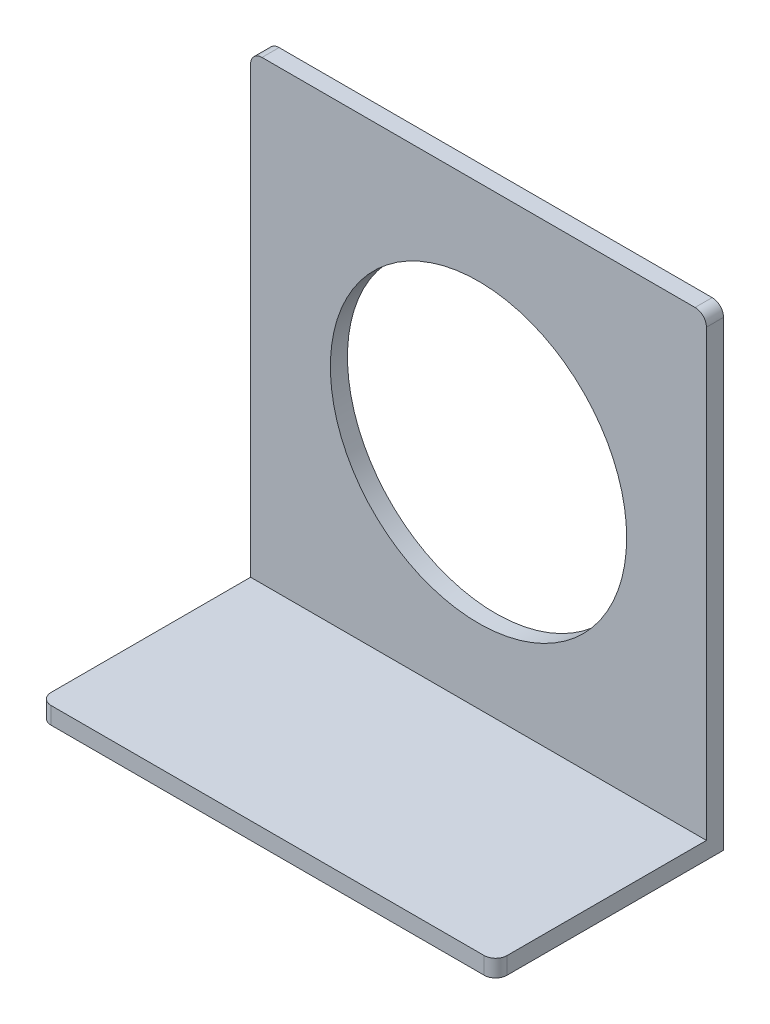
SolidWorks part; units mm, degrees
ref_plane "Front Plane" through (0, 0, 0) normal (0, 0, 1) x (1, 0, 0)
ref_plane "Top Plane" through (0, 0, 0) normal (0, 1, 0) x (1, 0, 0)
ref_plane "Right Plane" through (0, 0, 0) normal (1, 0, 0) x (0, 0, -1)
sketch "Sketch1" plane through (0, 0, 0) normal (0, 0, 1) x (1, 0, 0)
  line L1 (0, 0) -> (40, 0)
  line L2 (0, 0) -> (0, 41.5)
  line L3 (0, 41.5) -> (40, 41.5)
  line L4 (40, 0) -> (40, 41.5)
  dimension "D1" = 41.5
  dimension "D2" = 40
extrude "Boss-Extrude1" add sketch "Sketch1" along normal blind 1.5
sketch "Sketch2" plane through (0, 0, 1.5) normal (0, 0, 1) x (1, 0, 0)
  line L0 (40, 0) -> (40, 41.5) construction
  line L1 (0, 0) -> (40, 0)
  line L2 (0, 0) -> (0, 1.5)
  line L3 (0, 1.5) -> (40, 1.5)
  line L4 (40, 0) -> (40, 1.5)
  dimension "D1" = 1.5
extrude "Boss-Extrude2" add sketch "Sketch2" along normal blind 18.5
fillet "Fillet1" radius 1 1 edges at (0, 41.5, 0.75)
fillet "Fillet2" radius 1 3 edges at (40, 41.5, 0.75) (40, 0.75, 20) (0, 0.75, 20)
sketch "Sketch3" plane through (0, 0, 1.5) normal (0, 0, 1) x (1, 0, 0)
  line L0 (20, 41.5) -> (20, -4.055) construction
  line L1 (39, 41.5) -> (1, 41.5) construction
  line L2 (0, 21) -> (40, 21) construction
  line L3 (0, 40.5) -> (0, 1.5) construction
  line L4 (40, 1.5) -> (40, 40.5) construction
  circle A1 centre (20, 21) radius 13
extrude "Cut-Extrude1" cut sketch "Sketch3" against normal blind 1.5
